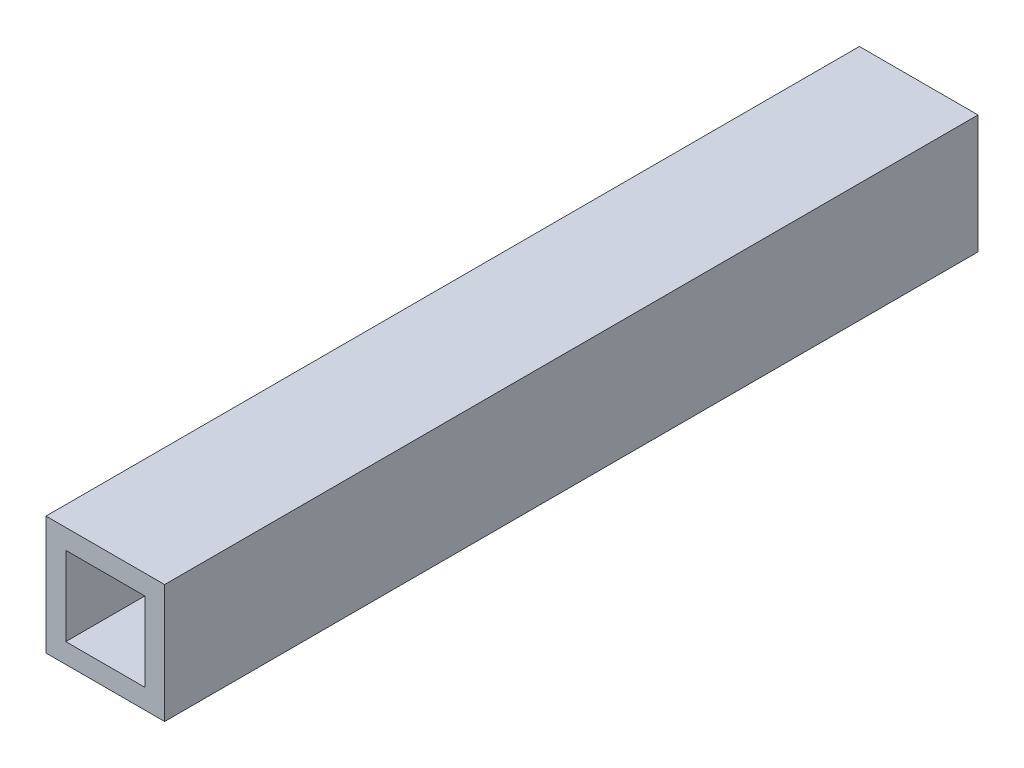
SolidWorks part; units mm, degrees
material "AISI 1010 Steel, hot rolled bar"
ref_plane "Front Plane" through (0, 0, 0) normal (0, 0, 1) x (1, 0, 0)
ref_plane "Top Plane" through (0, 0, 0) normal (0, 1, 0) x (1, 0, 0)
ref_plane "Right Plane" through (0, 0, 0) normal (1, 0, 0) x (0, 0, -1)
sketch "Sketch1" plane through (0, 0, 0) normal (0, 0, 1) x (1, 0, 0)
  line L1 (-15, 15) -> (15, 15)
  line L2 (-15, 15) -> (-15, -15)
  line L3 (-15, -15) -> (15, -15)
  line L4 (15, 15) -> (15, -15)
  line L5 (-15, 15) -> (15, -15) construction
  line L6 (-15, -15) -> (15, 15) construction
  line L7 (-10, 10) -> (10, 10)
  line L8 (-10, 10) -> (-10, -10)
  line L9 (-10, -10) -> (10, -10)
  line L10 (10, 10) -> (10, -10)
  line L11 (-10, 10) -> (10, -10) construction
  line L12 (-10, -10) -> (10, 10) construction
  point P0 (0, 0)
  point P6 (0, 0)
  dimension "D1" = 30
  dimension "D2" = 30
  dimension "D3" = 5
extrude "Boss-Extrude1" add sketch "Sketch1" along normal blind 205.7
